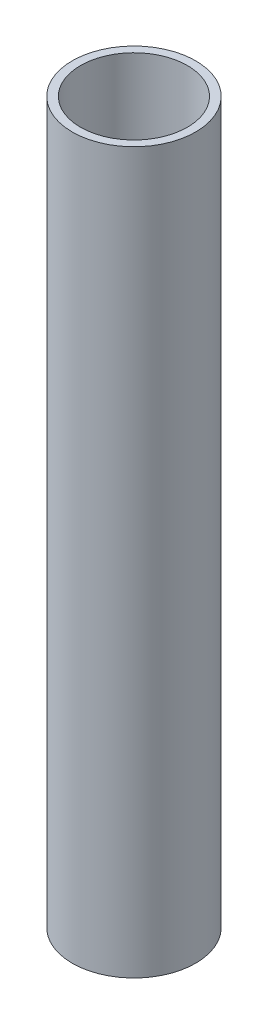
SolidWorks part; units mm, degrees
material "1060 Alloy"
ref_plane "Front Plane" through (0, 0, 0) normal (0, 0, 1) x (1, 0, 0)
ref_plane "Top Plane" through (0, 0, 0) normal (0, 1, 0) x (1, 0, 0)
ref_plane "Right Plane" through (0, 0, 0) normal (1, 0, 0) x (0, 0, -1)
sketch "Sketch1" plane through (0, 0, 0) normal (0, 1, 0) x (1, 0, 0)
  circle A0 centre (0, 0) radius 3
  circle A1 centre (0, 0) radius 2.6
  dimension "D1" = 6
  dimension "D2" = 5.2
extrude "Boss-Extrude1" add sketch "Sketch1" along normal blind 35
